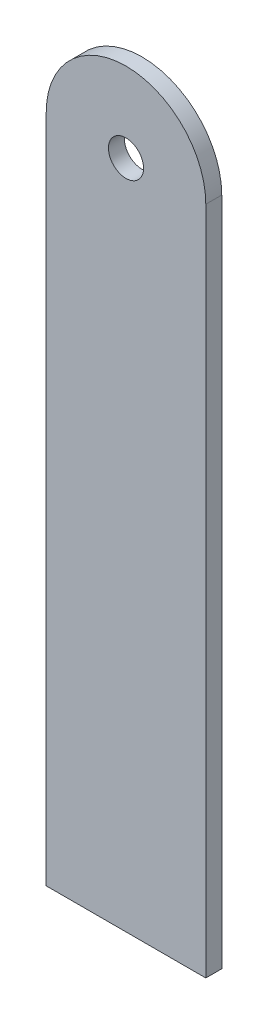
SolidWorks part; units mm, degrees
ref_plane "Front Plane" through (0, 0, 0) normal (0, 0, 1) x (1, 0, 0)
ref_plane "Top Plane" through (0, 0, 0) normal (0, 1, 0) x (1, 0, 0)
ref_plane "Right Plane" through (0, 0, 0) normal (1, 0, 0) x (0, 0, -1)
sketch "Sketch1" plane through (0, 0, 0) normal (0, 0, 1) x (1, 0, 0)
  line L0 (0, 0) -> (0, 210)
  line L1 (50, 210) -> (50, 0)
  line L2 (50, 0) -> (0, 0)
  arc A0 (0, 210) -> (50, 210) centre (25, 210) cw
  circle A1 centre (25, 210) radius 5.5
  dimension "D3" = 25
  dimension "D4" = 11
  dimension "D1" = 50
  dimension "D2" = 210
extrude "Boss-Extrude1" add sketch "Sketch1" along normal blind 5
